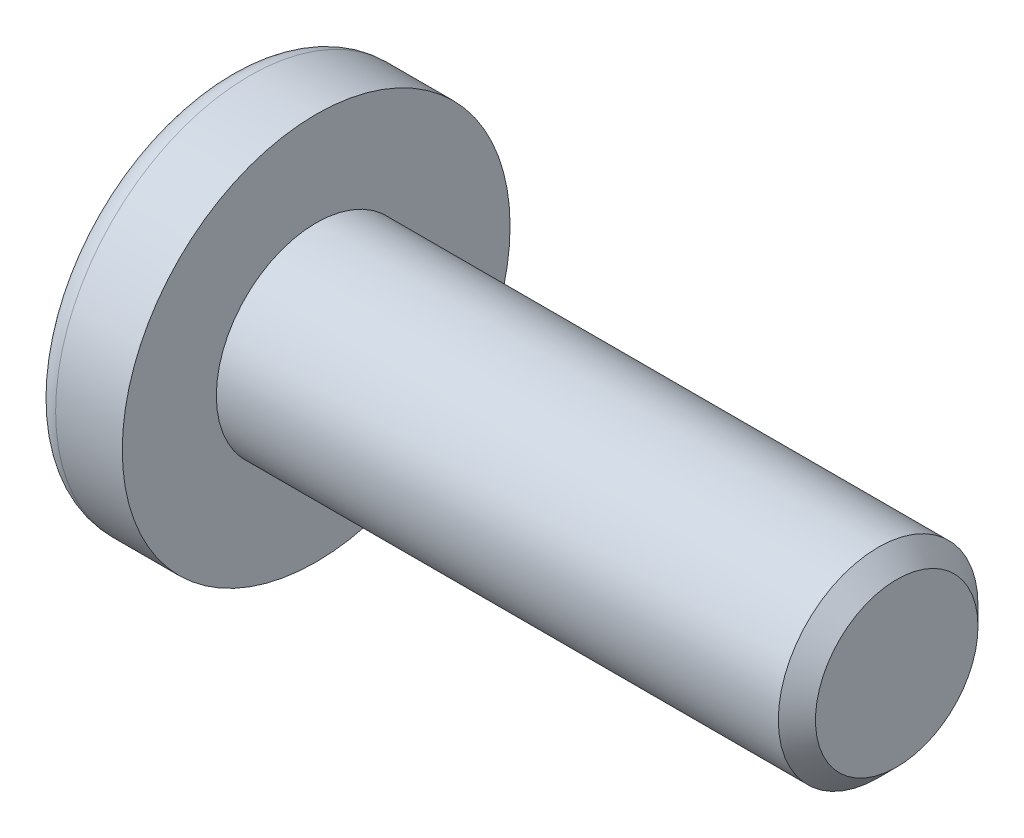
SolidWorks part; units mm, degrees
material "Alloy Steel"
ref_plane "Plane1" through (0, 0, 0) normal (0, 0, 1) x (1, 0, 0)
ref_plane "Plane2" through (0, 0, 0) normal (0, 1, 0) x (1, 0, 0)
ref_plane "Plane3" through (0, 0, 0) normal (1, 0, 0) x (0, 0, -1)
sketch "BodySke" plane through (0, 0, 0) normal (0, 0, 1) x (1, 0, 0)
  line L0 (1.5748, 1.0922) -> (1.5748, 2.1209)
  line L1 (1.8021, 6.35) -> (1.8021, -3.175) construction
  line L2 (-25.4, 0) -> (127, 0) construction
  line L3 (7.9248, 0) -> (0, 0)
  line L4 (1.5748, 1.0922) -> (7.9248, 1.0922)
  line L5 (7.9248, 1.0922) -> (7.9248, 0)
  line L6 (0.8457, 2.1209) -> (1.5748, 2.1209)
  line L7 (1.5748, -1.0922) -> (7.9248, -1.0922) construction
  line L8 (1.5748, 6.35) -> (1.5748, -3.175) construction
  arc A0 (0.6381, 2.0132) -> (0, 0) centre (3.495, 0) ccw
  arc A2 (0.6381, 2.0132) -> (0.8457, 2.1209) centre (0.8457, 1.8669) cw
  dimension "Head_fillet_rad" = 0.254
  dimension "Head_crown_rad" = 3.495
  dimension "Head_ht" = 1.5748
  dimension "Diameter" = 2.1844
  dimension "Length" = 6.35
  dimension "Head_dia" = 4.2418
  dimension "Advance" = 0.4547
  dimension "Thread_nom" = 6.35
revolve "Base-Revolve" add sketch "BodySke" angle 360 about L2
cosmetic thread "ThreadCosmetic" parameters "Thread_length"=5.8953, "Thread_minor"=1.6459
sketch "Sketch3" plane through (0, 0, 0) normal (1, 0, 0) x (0, 0, -1)
  line L0 (0.3429, -1.3843) -> (-0.3429, -1.3843)
  line L1 (0.3429, -1.3843) -> (0.3429, 1.3843)
  line L2 (-0.3429, 1.3843) -> (0.3429, 1.3843)
  line L3 (-0.3429, 1.3843) -> (-0.3429, -1.3843)
  dimension "D1" = 1.3843
  dimension "Cross_dia" = 2.7686
  dimension "D2" = 0.3429
  dimension "Cross_width" = 0.6858
ref_plane "Plane4" through (1.4986, 0, 0) normal (1, 0, 0) x (0, 0, -1)
sketch "Sketch4" plane through (1.4986, 0, 0) normal (1, 0, 0) x (0, 0, -1)
  line L0 (0.1714, -0.1715) -> (-0.1714, -0.1715)
  line L1 (0.1714, -0.1715) -> (0.1714, 0.1714)
  line L2 (-0.1714, 0.1714) -> (0.1714, 0.1714)
  line L3 (-0.1714, 0.1714) -> (-0.1714, -0.1715)
  dimension "D1" = 0.3429
  dimension "D2" = 0.3429
  dimension "D3" = 0.1714
  dimension "D4" = 0.1714
loft "Cut-Loft1" cut profiles "Sketch3", "Sketch4"
pattern_circular "CirPattern1" count 2 every 90 about axis through (0, 0, 0) along (1, 0, 0) of "Cut-Loft1"
chamfer "Chamfer1" distance 0.2032 angle 45 1 edges at (7.9248, 0, 1.0922)
equation "\"D1@Sketch3\" = \"Cross_dia@Sketch3\" / 2"
equation "\"D2@Sketch3\" = \"Cross_width@Sketch3\" / 2"
equation "\"D1@Sketch4\" = \"Cross_width@Sketch3\" *.5"
equation "\"D2@Sketch4\" = \"D1@Sketch4\""
equation "\"D3@Sketch4\" = \"D1@Sketch4\" / 2"
equation "\"D4@Sketch4\" = \"D2@Sketch4\" / 2"
equation "\"Thread_length@ThreadCosmetic\" = ((sgn( (\"Length@BodySke\" - \"Advance@BodySke\" ) - \"Thread_nom@BodySke\" )-1)*( (\"Length@BodySke\" - \"Advance@BodySke\" ) - \"Thread_nom@BodySke\" ))/-2+ \"Thread_nom@BodySke\""
